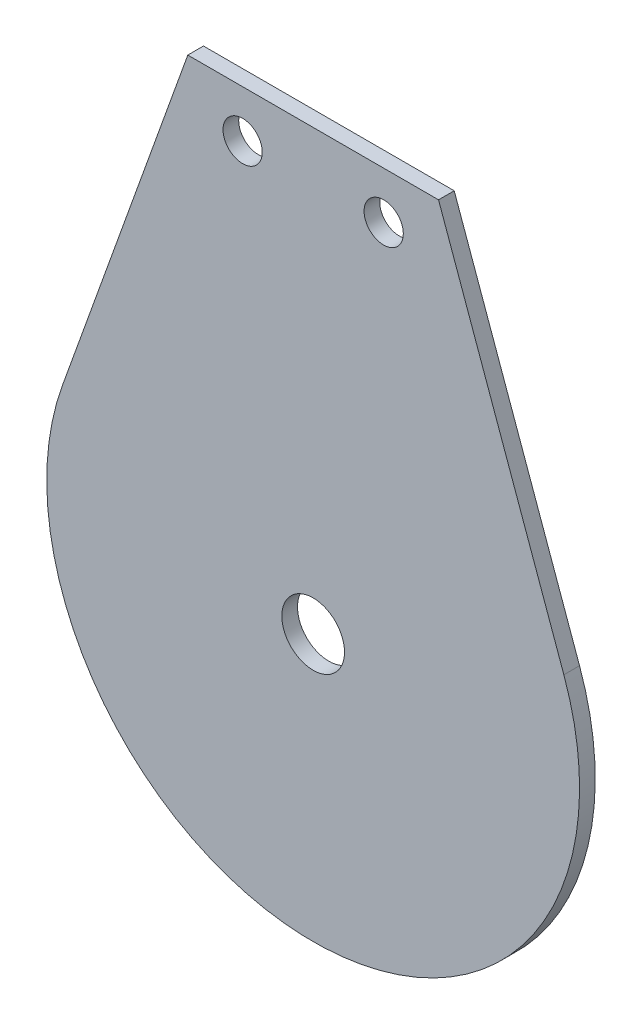
SolidWorks part; units mm, degrees
material "AISI 4340 Steel, normalized"
ref_plane "Front Plane" through (0, 0, 0) normal (0, 0, 1) x (1, 0, 0)
ref_plane "Top Plane" through (0, 0, 0) normal (0, 1, 0) x (1, 0, 0)
ref_plane "Right Plane" through (0, 0, 0) normal (1, 0, 0) x (0, 0, -1)
sketch "Sketch1" plane through (0, 0, 0) normal (0, 0, 1) x (1, 0, 0)
  line L0 (0, 54.6193) -> (0, -54.8794) construction
  line L1 (0, -55) -> (0, 55) construction
  line L2 (-25.4, 88.9) -> (25.4, 88.9)
  line L3 (25.4, 88.9) -> (50.7931, 18.2582)
  line L4 (-25.4, 88.9) -> (-50.7931, 18.2582)
  line L5 (55, 0) -> (-55, 0) construction
  arc A0 (-50.7931, 18.2582) -> (50.7931, 18.2582) centre (0, 0) ccw
  circle A1 centre (14.2875, 79.375) radius 3.9751
  circle A2 centre (-14.2875, 79.375) radius 3.9751
  circle A3 centre (0, 0) radius 6.35
  point P8 (0, 88.9)
  point P19 (42.5982, 33.1465)
  dimension "D2" = 7.9502
  dimension "D5" = 107.95
  dimension "D7" = 12.7
  dimension "D1" = 50.8
  dimension "D3" = 28.575
  dimension "D4" = 88.9
  dimension "D6" = 79.375
extrude "Boss-Extrude1" add sketch "Sketch1" along normal blind 3.175
